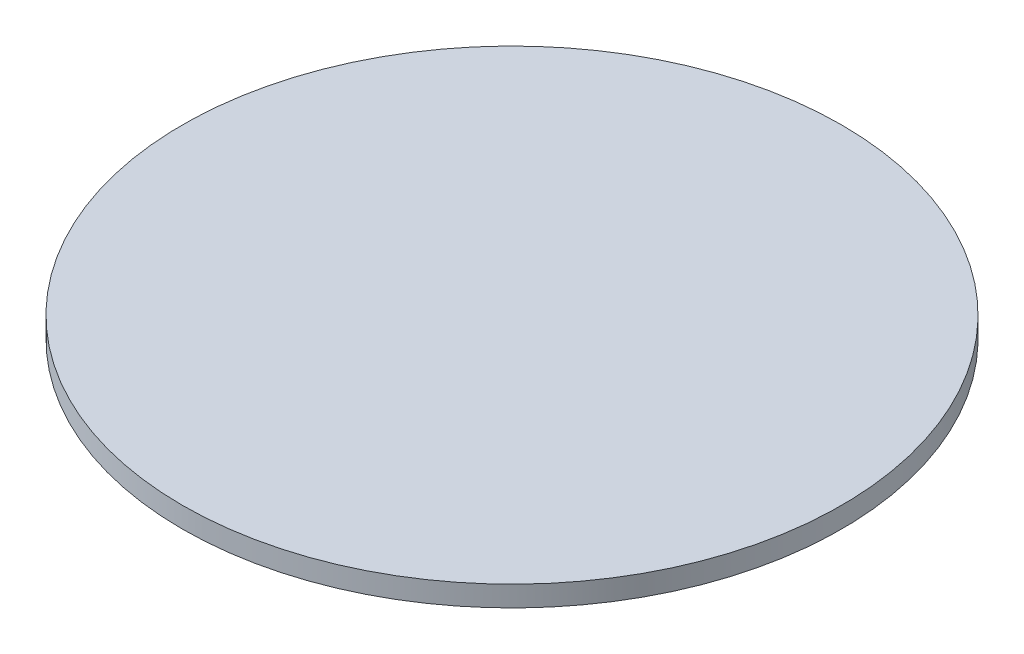
SolidWorks part; units mm, degrees
material "Mahogany"
ref_plane "Front" through (0, 0, 0) normal (0, 0, 1) x (1, 0, 0)
ref_plane "Top" through (0, 0, 0) normal (0, 1, 0) x (1, 0, 0)
ref_plane "Right" through (0, 0, 0) normal (1, 0, 0) x (0, 0, -1)
sketch "Sketch1" plane through (0, 0, 0) normal (0, 1, 0) x (1, 0, 0)
  circle A0 centre (0, 0) radius 101.6
  dimension "D1" = 203.2
extrude "Boss-Extrude1" add sketch "Sketch1" along normal blind 6.35
